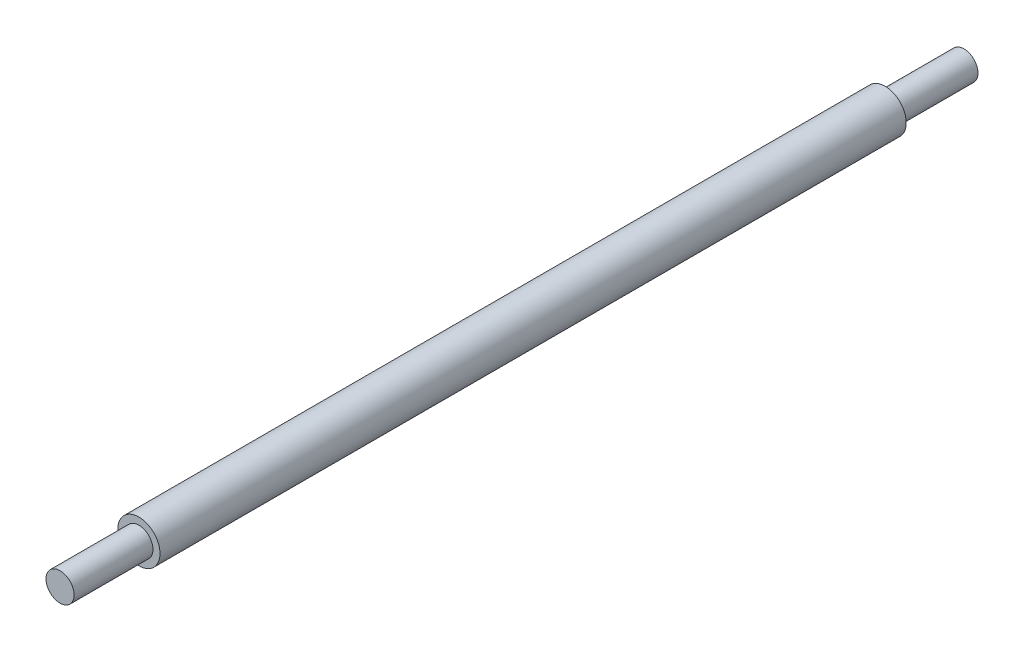
SolidWorks part; units mm, degrees
material "6061 Alloy"
ref_plane "Front" through (0, 0, 0) normal (0, 0, 1) x (1, 0, 0)
ref_plane "Top" through (0, 0, 0) normal (0, 1, 0) x (1, 0, 0)
ref_plane "Right" through (0, 0, 0) normal (1, 0, 0) x (0, 0, -1)
sketch "Sketch1" plane through (0, 0, 0) normal (0, 0, 1) x (1, 0, 0)
  circle A0 centre (0, 0) radius 9.525
  dimension "D1" = 19.05
extrude "Boss-Extrude1" add sketch "Sketch1" along normal blind 336.55
sketch "Sketch2" plane through (0, 0, 336.55) normal (0, 0, 1) x (1, 0, 0)
  circle A0 centre (0, 0) radius 6.35
  dimension "D1" = 12.7
extrude "Boss-Extrude2" add sketch "Sketch2" along normal blind 35.56
sketch "Sketch3" plane through (0, 0, 0) normal (0, 0, -1) x (-1, 0, 0)
  circle A0 centre (0, 0) radius 6.35
  dimension "D1" = 12.7
extrude "Boss-Extrude3" add sketch "Sketch3" along normal blind 35.56
